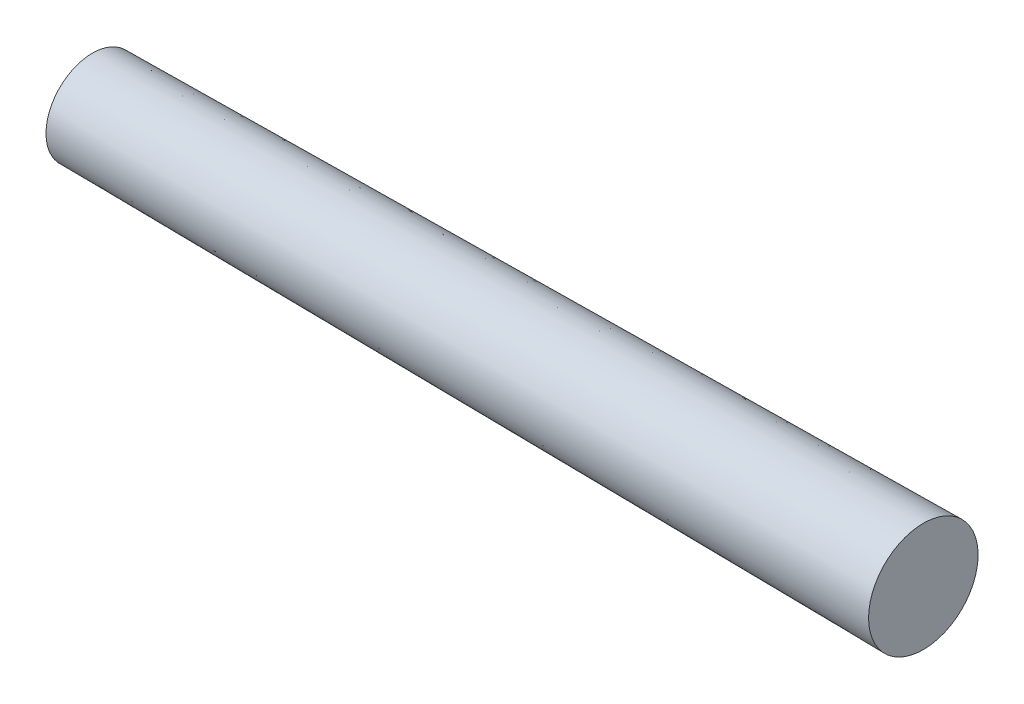
SolidWorks part; units mm, degrees
ref_plane "Front Plane" through (0, 0, 0) normal (0, 0, 1) x (1, 0, 0)
ref_plane "Top Plane" through (0, 0, 0) normal (0, 1, 0) x (1, 0, 0)
ref_plane "Right Plane" through (0, 0, 0) normal (1, 0, 0) x (0, 0, -1)
sketch "Sketch1" plane through (0, 0, 0) normal (0, 0, 1) x (1, 0, 0)
  line L0 (0, 0) -> (110, 0) construction
  line L1 (110, 7.25) -> (0, 6.15)
  line L2 (0, 6.15) -> (0, 0)
  line L3 (110, 7.25) -> (110, 0)
  line L4 (0, 0) -> (110, 0)
  dimension "D1" = 110
  dimension "D2" = 14.5
  dimension "D3" = 12.3
revolve "Revolve1" add sketch "Sketch1" angle 360 about L0
